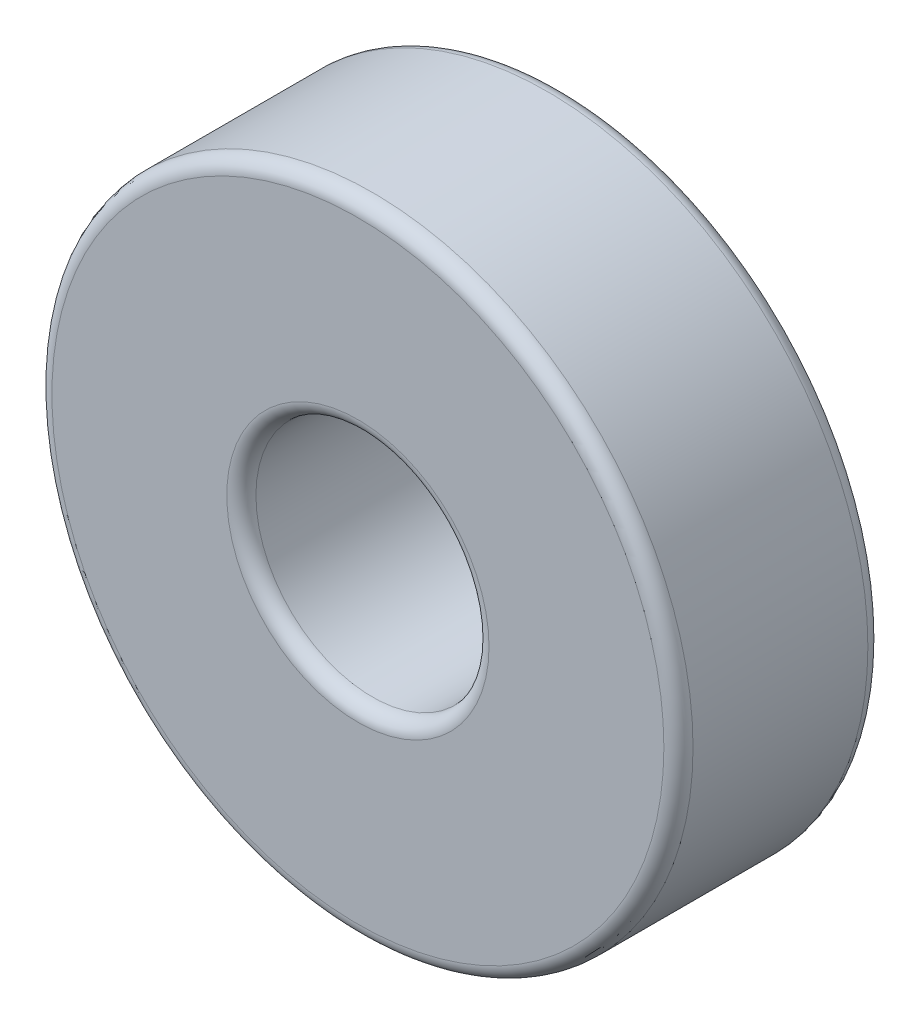
SolidWorks part; units mm, degrees
material "Хромистая нержавеющая сталь"
ref_plane "Спереди" through (0, 0, 0) normal (0, 0, 1) x (1, 0, 0)
ref_plane "Сверху" through (0, 0, 0) normal (0, 1, 0) x (1, 0, 0)
ref_plane "Справа" through (0, 0, 0) normal (1, 0, 0) x (0, 0, -1)
sketch "Эскиз1" plane through (0, 0, 0) normal (0, 0, 1) x (1, 0, 0)
  circle A0 centre (0, 0) radius 4
  circle A1 centre (0, 0) radius 11
  dimension "D1" = 8
  dimension "D2" = 22
extrude "Бобышка-Вытянуть1" add sketch "Эскиз1" along normal blind 7 contours A1 | A0
fillet "Скругление1" radius 0.5 4 edges at (4, 0, 0) (4, 0, 7) (11, 0, 0) (11, 0, 7)
